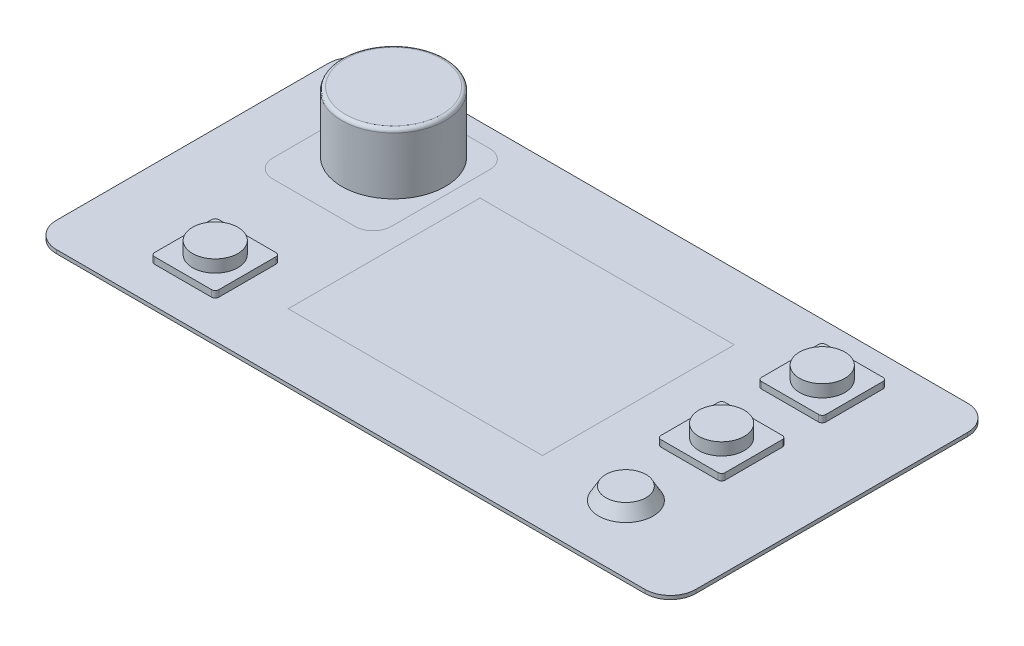
SolidWorks part; units mm, degrees
ref_plane "Front Plane" through (0, 0, 0) normal (0, 0, 1) x (1, 0, 0)
ref_plane "Top Plane" through (0, 0, 0) normal (0, 1, 0) x (1, 0, 0)
ref_plane "Right Plane" through (0, 0, 0) normal (1, 0, 0) x (0, 0, -1)
sketch "Sketch1" plane through (0, 0, 0) normal (0, 1, 0) x (1, 0, 0)
  line L1 (-88, -44.4) -> (88, -44.4)
  line L2 (-88, -44.4) -> (-88, 44.4)
  line L3 (-88, 44.4) -> (88, 44.4)
  line L4 (88, -44.4) -> (88, 44.4)
  line L5 (-88, -44.4) -> (88, 44.4) construction
  line L6 (-88, 44.4) -> (88, -44.4) construction
  point P0 (0, 0)
  dimension "D1" = 176
  dimension "D2" = 88.8
extrude "Boss-Extrude1" add sketch "Sketch1" along normal blind 1
sketch "Sketch2" plane through (0, 1, 0) normal (0, 1, 0) x (1, 0, 0)
  line L0 (-69.0943, 38.4) -> (49930.9057, 38.4) construction
  line L1 (-71, 24.6708) -> (-71, 50024.6708) construction
  line L2 (88, 44.4) -> (-88, 44.4) construction
  line L3 (-88, 44.4) -> (-88, -44.4) construction
  circle A0 centre (-56.75, 24.15) radius 14.25
  dimension "D1" = 28.5
  dimension "D2" = 6
  dimension "D3" = 17
extrude "Boss-Extrude2" add sketch "Sketch2" along normal blind 16.7
fillet "Fillet1" radius 1 1 edges at (-56.75, 17.7, -9.9)
sketch "Sketch3" plane through (0, 1, 0) normal (0, 1, 0) x (1, 0, 0)
  line L0 (-88, 44.4) -> (-88, -44.4) construction
  line L1 (-65, -34.4) -> (-47.3, -34.4)
  line L2 (-65, -34.4) -> (-65, -16.7)
  line L3 (-65, -16.7) -> (-47.3, -16.7)
  line L4 (-47.3, -34.4) -> (-47.3, -16.7)
  line L5 (-65, -34.4) -> (-47.3, -16.7) construction
  line L6 (-65, -16.7) -> (-47.3, -34.4) construction
  line L7 (-88, -44.4) -> (88, -44.4) construction
  line L8 (88, -44.4) -> (88, 44.4) construction
  line L9 (48.3, 19.4) -> (66, 19.4)
  line L10 (48.3, 19.4) -> (48.3, 37.1)
  line L11 (48.3, 37.1) -> (66, 37.1)
  line L12 (66, 19.4) -> (66, 37.1)
  line L13 (48.3, 19.4) -> (66, 37.1) construction
  line L14 (48.3, 37.1) -> (66, 19.4) construction
  line L15 (48.3, -8.3) -> (66, -8.3)
  line L16 (48.3, -8.3) -> (48.3, 9.4)
  line L17 (48.3, 9.4) -> (66, 9.4)
  line L18 (66, -8.3) -> (66, 9.4)
  line L19 (48.3, -8.3) -> (66, 9.4) construction
  line L20 (48.3, 9.4) -> (66, -8.3) construction
  line L21 (88, 44.4) -> (-88, 44.4) construction
  point P0 (-56.15, -25.55)
  point P9 (57.15, 28.25)
  point P14 (57.15, 0.55)
  point P21 (57.15, 37.1)
  dimension "D1" = 17.7
  dimension "D2" = 17.7
  dimension "D3" = 23
  dimension "D4" = 10
  dimension "D5" = 17.7
  dimension "D6" = 17.7
  dimension "D7" = 17.7
  dimension "D8" = 17.7
  dimension "D9" = 22
  dimension "D10" = 22
  dimension "D11" = 7.3
  dimension "D12" = 10
extrude "Boss-Extrude3" add sketch "Sketch3" along normal blind 1.8
fillet "Fillet2" radius 1 12 edges at (-47.3, 1.9, 16.7) (-47.3, 1.9, 34.4) (-65, 1.9, 16.7) (-65, 1.9, 34.4) (66, 1.9, -37.1) (66, 1.9, -9.4) (66, 1.9, -19.4) (48.3, 1.9, -37.1) (48.3, 1.9, -19.4) (48.3, 1.9, -9.4) (48.3, 1.9, 8.3) (66, 1.9, 8.3)
fillet "Fillet3" radius 7 4 edges at (88, 0.5, -44.4) (88, 0.5, 44.4) (-88, 0.5, -44.4) (-88, 0.5, 44.4)
sketch "Sketch4" plane through (0, 2.8, 0) normal (0, 1, 0) x (1, 0, 0)
  line L0 (-56.15, -16.7) -> (-56.15, 49983.3) construction
  line L1 (-48.3, -16.7) -> (-64, -16.7) construction
  line L2 (-65, -25.55) -> (49935, -25.55) construction
  line L3 (-65, -17.7) -> (-65, -33.4) construction
  line L4 (57.15, 37.1) -> (57.15, 50037.1) construction
  line L5 (65, 37.1) -> (49.3, 37.1) construction
  line L6 (48.3, 28.25) -> (50048.3, 28.25) construction
  line L7 (48.3, 36.1) -> (48.3, 20.4) construction
  line L8 (48.3, 0.55) -> (50048.3, 0.55) construction
  line L9 (48.3, 8.4) -> (48.3, -7.3) construction
  circle A0 centre (-56.15, -25.55) radius 6.25
  circle A1 centre (57.15, 28.25) radius 6.25
  circle A2 centre (57.15, 0.55) radius 6.25
  point P4 (-56.15, -16.7)
  point P9 (-65, -25.55)
  point P16 (57.15, 37.1)
  point P21 (48.3, 28.25)
  point P26 (48.3, 0.55)
  dimension "D1" = 12.5
  dimension "D2" = 12.5
  dimension "D3" = 12.5
extrude "Boss-Extrude4" add sketch "Sketch4" along normal blind 3.4
sketch "Sketch5" plane through (0, 1, 0) normal (0, 1, 0) x (1, 0, 0)
  line L0 (-81, -44.4) -> (81, -44.4) construction
  line L1 (-35, -26.6) -> (35, -26.6)
  line L2 (-35, -26.6) -> (-35, 26.2)
  line L3 (-35, 26.2) -> (35, 26.2)
  line L4 (35, -26.6) -> (35, 26.2)
  line L5 (-35, -26.6) -> (35, 26.2) construction
  line L6 (-35, 26.2) -> (35, -26.6) construction
  line L7 (0, 0) -> (0, 50000) construction
  point P0 (0, -0.2)
  dimension "D1" = 70
  dimension "D2" = 52.8
  dimension "D3" = 17.8
split line "Split Line1"
sketch "Sketch7" plane through (0, 1, 0) normal (0, 1, 0) x (1, 0, 0)
  line L0 (57.15, 28.25) -> (57.15, 50028.25) construction
  line L1 (57.15, -18.3) -> (50057.15, -18.3) construction
  line L2 (49.3, -8.3) -> (65, -8.3) construction
  circle A0 centre (57.15, -25.8) radius 7.5
  dimension "D1" = 15
  dimension "D2" = 10
extrude "Boss-Extrude5" add sketch "Sketch7" along normal blind 3.4 draft 30 contours A0
sketch "Sketch8" plane through (0, 1, 0) normal (0, 1, 0) x (1, 0, 0)
  line L0 (-56.75, 24.15) -> (-56.75, 50024.15) construction
  line L1 (-68.0688, 39.3212) -> (-45.4312, 39.3212)
  line L2 (-73.0688, 34.3212) -> (-73.0688, 7.2178)
  line L3 (-68.0688, 2.2178) -> (-45.4312, 2.2178)
  line L4 (-40.4312, 34.3212) -> (-40.4312, 7.2178)
  line L5 (-73.0688, 39.3212) -> (-40.4312, 2.2178) construction
  line L6 (-73.0688, 2.2178) -> (-40.4312, 39.3212) construction
  arc A0 (-73.0688, 7.2178) -> (-68.0688, 2.2178) centre (-68.0688, 7.2178) ccw
  arc A1 (-40.4312, 7.2178) -> (-45.4312, 2.2178) centre (-45.4312, 7.2178) cw
  arc A2 (-40.4312, 34.3212) -> (-45.4312, 39.3212) centre (-45.4312, 34.3212) ccw
  arc A3 (-68.0688, 39.3212) -> (-73.0688, 34.3212) centre (-68.0688, 34.3212) ccw
  point P4 (-56.75, 20.7695)
  dimension "D1" = 5
split line "Split Line2"
sketch "Sketch10" plane through (0, 1, 0) normal (0, 1, 0) x (1, 0, 0)
  line L0 (0, -44.4) -> (0, -102.4) construction
  line L1 (-81, -44.4) -> (81, -44.4) construction
sketch "Sketch11" plane through (0, 0, 0) normal (1, 0, 0) x (0, 0, -1)
  line L0 (-102.4, 1) -> (-102.4, 50001) construction
